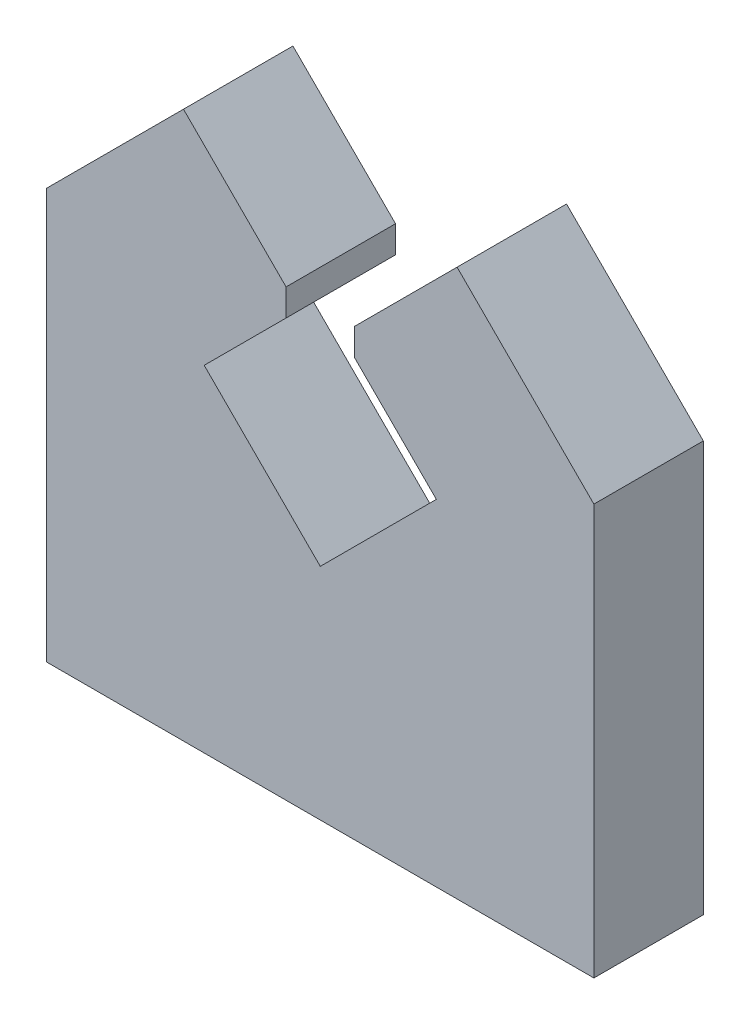
SolidWorks part; units mm, degrees
ref_plane "Front Plane" through (0, 0, 0) normal (0, 0, 1) x (1, 0, 0)
ref_plane "Top Plane" through (0, 0, 0) normal (0, 1, 0) x (1, 0, 0)
ref_plane "Right Plane" through (0, 0, 0) normal (1, 0, 0) x (0, 0, -1)
sketch "Sketch1" plane through (0, 0, 0) normal (0, 0, 1) x (1, 0, 0)
  line L0 (0, 300) -> (100, 400)
  line L1 (0, 0) -> (400, 0)
  line L2 (0, 0) -> (0, 300)
  line L3 (100, 400) -> (300, 400) construction
  line L4 (400, 0) -> (400, 300)
  line L5 (100, 400) -> (175, 325)
  line L6 (175, 325) -> (175, 305.2944)
  line L7 (175, 305.2944) -> (115.1472, 245.4416)
  line L8 (115.1472, 245.4416) -> (200, 160.5887)
  line L9 (200, 160.5887) -> (284.8528, 245.4416)
  line L10 (284.8528, 245.4416) -> (225, 305.2944)
  line L11 (225, 305.2944) -> (225, 325)
  line L12 (225, 325) -> (300, 400)
  line L13 (300, 400) -> (400, 300)
  line L14 (200, 400) -> (200, 0) construction
  dimension "D2" = 400
  dimension "D3" = 50
  dimension "D4" = 100
  dimension "D5" = 100
  dimension "D6" = 135
  dimension "D7" = 135
  dimension "D8" = 120
  dimension "D9" = 120
  dimension "D10" = 120
  dimension "D11" = 400
extrude "Boss-Extrude1" add sketch "Sketch1" along normal blind 80 contours L0 L5 L6 L7 L8 L9 L10 L11 L12 L13 L4 L1 L2
ref_plane "Plane1" through (0, 0, 40) normal (0, 0, -1) x (-1, 0, 0)
equation "\"D6@Sketch1\"=\"D7@Sketch1\""
equation "\"D9@Sketch1\"=\"D8@Sketch1\""
